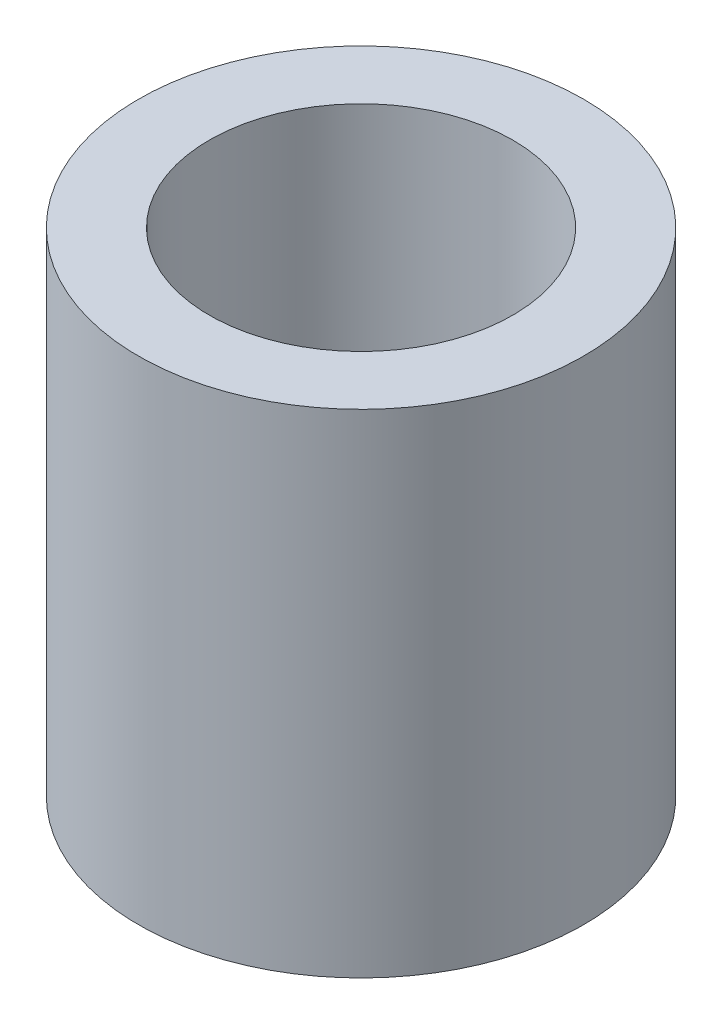
SolidWorks part; units mm, degrees
ref_plane "Front Plane" through (0, 0, 0) normal (0, 0, 1) x (1, 0, 0)
ref_plane "Top Plane" through (0, 0, 0) normal (0, 1, 0) x (1, 0, 0)
ref_plane "Right Plane" through (0, 0, 0) normal (1, 0, 0) x (0, 0, -1)
sketch "Sketch1" plane through (0, 0, 0) normal (0, 0, 1) x (1, 0, 0)
  line L0 (-4.5, 0) -> (-4.5, 14.605)
  line L1 (-4.5, 14.605) -> (-6.6, 14.605)
  line L2 (-6.6, 14.605) -> (-6.6, 0)
  line L3 (-6.6, 0) -> (-4.5, 0)
  line L4 (-4.5, 0) -> (0, 0) construction
  line L5 (0, 0) -> (0, 13.4348) construction
  dimension "D1" = 4.5
  dimension "D2" = 2.1
  dimension "D3" = 14.605
revolve "Revolve1" add sketch "Sketch1" angle 360 about L5
